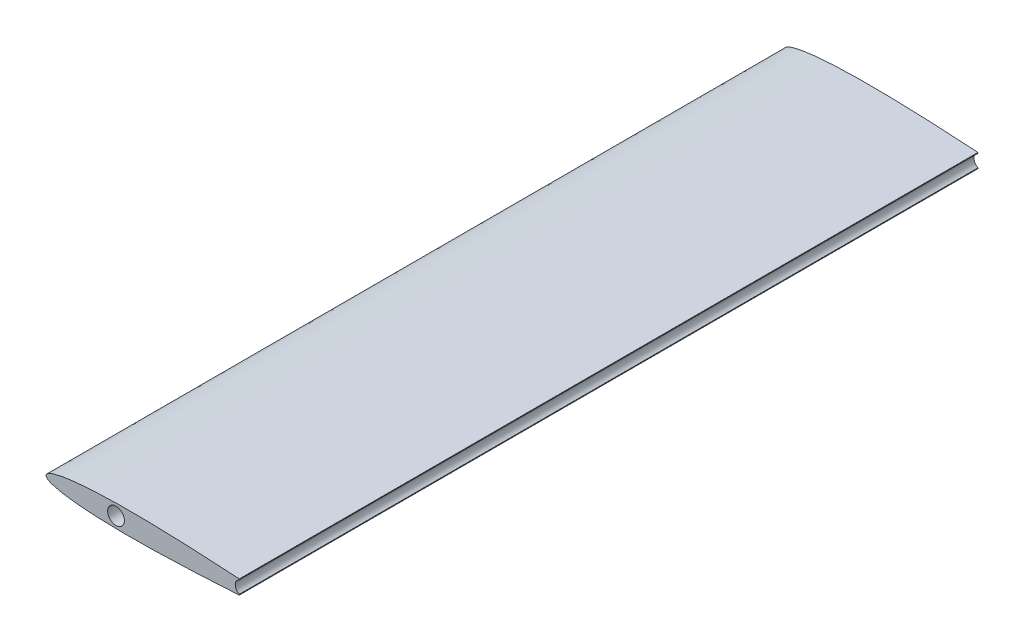
SolidWorks part; units mm, degrees
material "Foam"
ref_plane "Piano frontale" through (0, 0, 0) normal (0, 0, 1) x (1, 0, 0)
ref_plane "Piano superiore" through (0, 0, 0) normal (0, 1, 0) x (1, 0, 0)
ref_plane "Piano destro" through (0, 0, 0) normal (1, 0, 0) x (0, 0, -1)
curve "Curva1"
  spline degree 3 poles (100, 0.084, 0) (98.3335, 0.2367, 0) (95.0012, 0.5422, 0) (88.3356, 1.1109, 0) (80.0033, 1.7636, 0) (70.003, 2.4579, 0) (60.0031, 3.0617, 0) (50.003, 3.5521, 0) (40.0026, 3.9029, 0) (31.667, 4.0253, 0) (24.9992, 3.9769, 0) (19.9978, 3.845, 0) (14.9934, 3.5925, 0) (10.8272, 3.2377, 0) (7.4891, 2.814, 0) (4.9936, 2.4037, 0) (2.8496, 1.8679, 0) (1.1654, 1.321, 0) (-0.6646, 0, 0) (1.1654, -1.321, 0) (2.8496, -1.8679, 0) (4.9936, -2.4037, 0) (7.4891, -2.814, 0) (10.8272, -3.2377, 0) (14.9934, -3.5925, 0) (19.9978, -3.845, 0) (24.9992, -3.9769, 0) (31.667, -4.0253, 0) (40.0026, -3.9029, 0) (50.003, -3.5521, 0) (60.0031, -3.0617, 0) (70.003, -2.4579, 0) (80.0033, -1.7636, 0) (88.3356, -1.1109, 0) (95.0012, -0.5422, 0) (98.3335, -0.2367, 0) (100, -0.084, 0) knots 0 0 0 0 0.024876 0.049742 0.099443 0.149112 0.198751 0.248359 0.297937 0.347491 0.372267 0.397051 0.421859 0.446731 0.45922 0.471791 0.48456 0.491195 0.5 0.508805 0.51544 0.528209 0.54078 0.553269 0.578141 0.602949 0.627733 0.652509 0.702063 0.751641 0.801249 0.850888 0.900557 0.950258 0.975124 1 1 1 1
sketch "Schizzo1" plane through (0, 0, 0) normal (0, 0, 1) x (1, 0, 0)
  line L0 (70, 2.443) -> (70, -2.443) construction
  arc A1 (70, 2.443) -> (70, -2.443) centre (70, 0) ccw
  spline S0 degree 3 poles (1029.3323, 4889.466) (420.5539, -80.0474) (258.4436, -13.4031) (88.3356, 1.1109) (80.0033, 1.7636) (70.003, 2.4579) (60.0031, 3.0617) (50.003, 3.5521) (40.0026, 3.9029) (31.667, 4.0253) (24.9992, 3.9769) (19.9978, 3.845) (14.9934, 3.5925) (10.8272, 3.2377) (7.4891, 2.814) (4.9936, 2.4037) (2.8496, 1.8679) (1.1654, 1.321) (-0.6646, 0) (1.1654, -1.321) (2.8496, -1.8679) (4.9936, -2.4037) (7.4891, -2.814) (10.8272, -3.2377) (14.9934, -3.5925) (19.9978, -3.845) (24.9992, -3.9769) (31.667, -4.0253) (40.0026, -3.9029) (50.003, -3.5521) (60.0031, -3.0617) (70.003, -2.4579) (80.0033, -1.7636) (88.3356, -1.1109) (258.4415, 13.4029) (420.5498, 80.0458) (1029.3091, -4889.2764) knots -2.438368 -2.438368 -2.438368 -2.438368 0.024876 0.049742 0.099443 0.149112 0.198751 0.248359 0.297937 0.347491 0.372267 0.397051 0.421859 0.446731 0.45922 0.471791 0.48456 0.491195 0.5 0.508805 0.51544 0.528209 0.54078 0.553269 0.578141 0.602949 0.627733 0.652509 0.702063 0.751641 0.801249 0.850888 0.900557 0.950258 0.975124 3.438336 3.438336 3.438336 3.438336 only from (100, 0.084) to (100, -0.084) construction
  spline S1 degree 3 poles (70, 2.443) (66.6677, 2.6593) (60.0031, 3.0617) (50.003, 3.5521) (40.0026, 3.9029) (31.667, 4.0253) (24.9992, 3.9769) (19.9978, 3.845) (14.9934, 3.5925) (10.8272, 3.2377) (7.4891, 2.814) (4.9936, 2.4037) (2.8496, 1.8679) (1.1654, 1.321) (-0.6646, 0) (1.1654, -1.321) (2.8496, -1.8679) (4.9936, -2.4037) (7.4891, -2.814) (10.8272, -3.2377) (14.9934, -3.5925) (19.9978, -3.845) (24.9992, -3.9769) (31.667, -4.0253) (40.0026, -3.9029) (50.003, -3.5521) (60.0031, -3.0617) (66.6677, -2.6593) (70, -2.443) knots 0.149112 0.149112 0.149112 0.149112 0.198751 0.248359 0.297937 0.347491 0.372267 0.397051 0.421859 0.446731 0.45922 0.471791 0.48456 0.491195 0.5 0.508805 0.51544 0.528209 0.54078 0.553269 0.578141 0.602949 0.627733 0.652509 0.702063 0.751641 0.801249 0.850888 0.850888 0.850888 0.850888
  dimension "D2" = 4.886
extrude "CorpoFoam" add sketch "Schizzo1" along normal blind 263.67
sketch "Schizzo2" plane through (0, 0, 263.67) normal (0, 0, 1) x (1, 0, 0)
  line L0 (72, 0) -> (70, 0) construction
  line L1 (72, 2.5074) -> (69, 2.5074)
  line L2 (72, 2.5074) -> (72, -2.5074)
  line L3 (72, -2.5074) -> (69, -2.5074)
  line L4 (69, 2.5074) -> (69, -2.5074)
  arc A0 (70, 2.443) -> (70, -2.443) centre (70, 0) ccw construction
  spline S0 degree 3 poles (70, 2.443) (66.6677, 2.6593) (60.0031, 3.0617) (50.003, 3.5521) (40.0026, 3.9029) (31.667, 4.0253) (24.9992, 3.9769) (19.9978, 3.845) (14.9934, 3.5925) (10.8272, 3.2377) (7.4891, 2.814) (4.9936, 2.4037) (2.8496, 1.8679) (1.1654, 1.321) (-0.6646, 0) (1.1654, -1.321) (2.8496, -1.8679) (4.9936, -2.4037) (7.4891, -2.814) (10.8272, -3.2377) (14.9934, -3.5925) (19.9978, -3.845) (24.9992, -3.9769) (31.667, -4.0253) (40.0026, -3.9029) (50.003, -3.5521) (60.0031, -3.0617) (66.6677, -2.6593) (70, -2.443) knots 0.149112 0.149112 0.149112 0.149112 0.198751 0.248359 0.297937 0.347491 0.372267 0.397051 0.421859 0.446731 0.45922 0.471791 0.48456 0.491195 0.5 0.508805 0.51544 0.528209 0.54078 0.553269 0.578141 0.602949 0.627733 0.652509 0.702063 0.751641 0.801249 0.850888 0.850888 0.850888 0.850888 construction
  dimension "D1" = 3
  dimension "D2" = 1
extrude "SmussoPosteriore" cut sketch "Schizzo2" against normal through all
sketch "Schizzo3" plane through (0, 0, 263.67) normal (0, 0, 1) x (1, 0, 0)
  circle A0 centre (25, 0) radius 3
  dimension "D1" = 6
  dimension "D2" = 25
extrude "ForoLongherone" cut sketch "Schizzo3" against normal through all
ref_plane "PianoMedio" through (0, 0, 140) normal (0, 0, 1) x (1, 0, 0)
